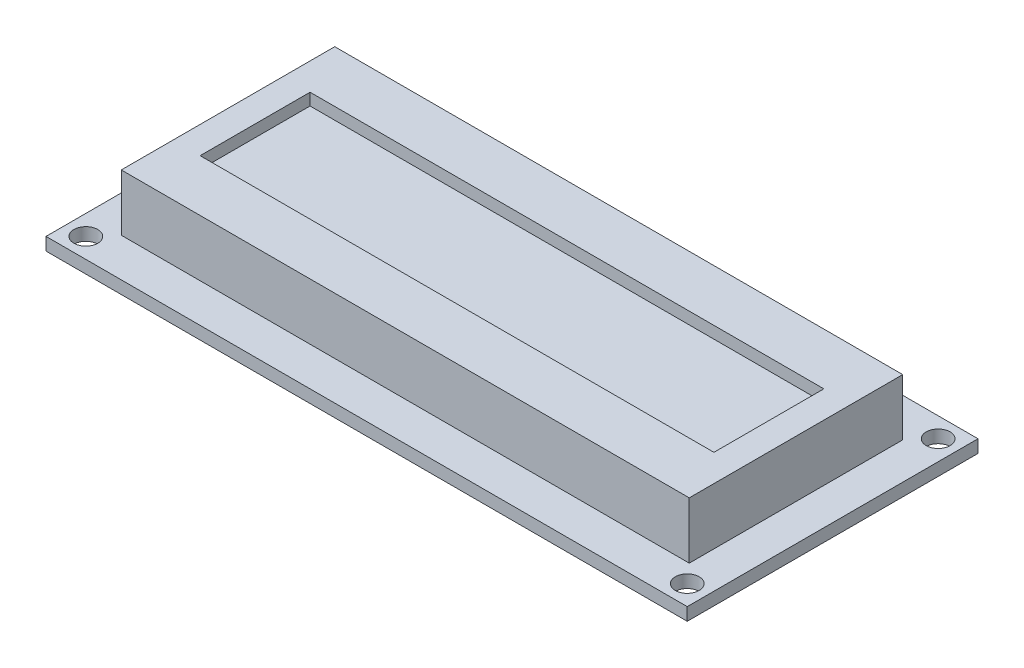
SolidWorks part; units mm, degrees
ref_plane "Front Plane" through (0, 0, 0) normal (0, 0, 1) x (1, 0, 0)
ref_plane "Top Plane" through (0, 0, 0) normal (0, 1, 0) x (1, 0, 0)
ref_plane "Right Plane" through (0, 0, 0) normal (1, 0, 0) x (0, 0, -1)
sketch "Sketch1" plane through (0, 0, 0) normal (0, 1, 0) x (1, 0, 0)
  line L1 (-40.25, -18.25) -> (40.25, -18.25)
  line L2 (-40.25, -18.25) -> (-40.25, 18.25)
  line L3 (-40.25, 18.25) -> (40.25, 18.25)
  line L4 (40.25, -18.25) -> (40.25, 18.25)
  line L5 (-40.25, -18.25) -> (40.25, 18.25) construction
  line L6 (-40.25, 18.25) -> (40.25, -18.25) construction
  point P0 (0, 0)
  dimension "D1" = 36.5
  dimension "D2" = 80.5
extrude "Boss-Extrude1" add sketch "Sketch1" along normal blind 1.6
sketch "Sketch2" plane through (0, 1.6, 0) normal (0, 1, 0) x (1, 0, 0)
  line L0 (-40.25, 18.25) -> (-40.25, -18.25) construction
  line L1 (40.25, 18.25) -> (-40.25, 18.25) construction
  line L2 (-40.25, -18.25) -> (40.25, -18.25) construction
  line L3 (40.25, -18.25) -> (40.25, 18.25) construction
  circle A0 centre (-37.75, 15.75) radius 1.5
  circle A1 centre (-37.75, -15.75) radius 1.5
  circle A2 centre (37.75, 15.75) radius 1.5
  circle A3 centre (37.75, -15.75) radius 1.5
  dimension "D1" = 3
  dimension "D6" = 3
  dimension "D9" = 3
  dimension "D10" = 3
  dimension "D2" = 2.5
  dimension "D3" = 2.5
  dimension "D4" = 2.5
  dimension "D5" = 2.5
  dimension "D7" = 2.5
  dimension "D8" = 2.5
  dimension "D11" = 2.5
  dimension "D12" = 2.5
extrude "Cut-Extrude1" cut sketch "Sketch2" against normal blind 1.6
sketch "Sketch3" plane through (0, 1.6, 0) normal (0, 1, 0) x (1, 0, 0)
  line L1 (-35.65, -13.4) -> (35.65, -13.4)
  line L2 (-35.65, -13.4) -> (-35.65, 13.4)
  line L3 (-35.65, 13.4) -> (35.65, 13.4)
  line L4 (35.65, -13.4) -> (35.65, 13.4)
  line L5 (-35.65, -13.4) -> (35.65, 13.4) construction
  line L6 (-35.65, 13.4) -> (35.65, -13.4) construction
  point P0 (0, 0)
  dimension "D1" = 26.8
  dimension "D2" = 71.3
extrude "Boss-Extrude2" add sketch "Sketch3" along normal blind 7.1
sketch "Sketch4" plane through (0, 1.6, 0) normal (0, 1, 0) x (1, 0, 0)
  line L0 (-40.25, 18.25) -> (-40.25, -18.25) construction
  line L1 (40.25, 18.25) -> (-40.25, 18.25) construction
  circle A0 centre (-32.25, 15.75) radius 0.5
  circle A1 centre (-29.71, 15.75) radius 0.5
  circle A2 centre (-27.17, 15.75) radius 0.5
  circle A3 centre (-24.63, 15.75) radius 0.5
  circle A4 centre (-22.09, 15.75) radius 0.5
  circle A5 centre (-19.55, 15.75) radius 0.5
  circle A6 centre (-17.01, 15.75) radius 0.5
  circle A7 centre (-14.47, 15.75) radius 0.5
  circle A8 centre (-11.93, 15.75) radius 0.5
  circle A9 centre (-9.39, 15.75) radius 0.5
  circle A10 centre (-6.85, 15.75) radius 0.5
  circle A11 centre (-4.31, 15.75) radius 0.5
  circle A12 centre (-1.77, 15.75) radius 0.5
  circle A13 centre (0.77, 15.75) radius 0.5
  circle A14 centre (3.31, 15.75) radius 0.5
  circle A15 centre (5.85, 15.75) radius 0.5
  dimension "D2" = 1
  dimension "D1" = 8
  dimension "D3" = 2.5
  dimension "D4" = 16
extrude "Cut-Extrude2" cut sketch "Sketch4" against normal blind 7.1
sketch "Sketch5" plane through (0, 8.7, 0) normal (0, 1, 0) x (1, 0, 0)
  line L1 (-32.25, -6.9) -> (32.25, -6.9)
  line L2 (-32.25, -6.9) -> (-32.25, 6.9)
  line L3 (-32.25, 6.9) -> (32.25, 6.9)
  line L4 (32.25, -6.9) -> (32.25, 6.9)
  line L5 (-32.25, -6.9) -> (32.25, 6.9) construction
  line L6 (-32.25, 6.9) -> (32.25, -6.9) construction
  point P0 (0, 0)
  dimension "D1" = 13.8
  dimension "D2" = 64.5
extrude "Cut-Extrude3" cut sketch "Sketch5" against normal blind 1.5
